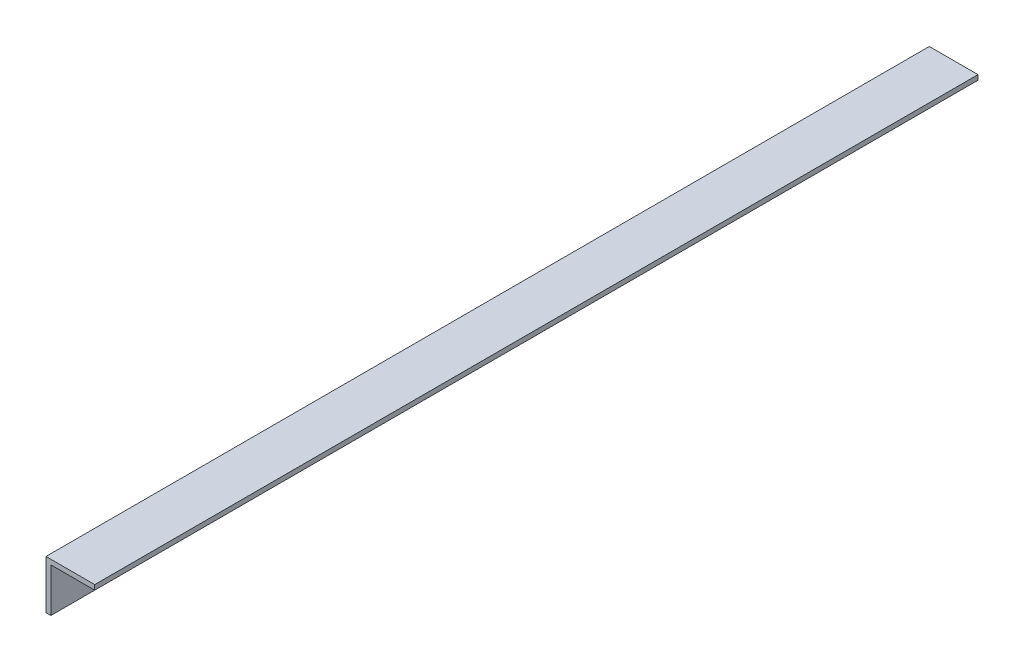
SolidWorks part; units mm, degrees
material "6061 Alloy"
ref_plane "Front Plane" through (0, 0, 0) normal (0, 0, 1) x (1, 0, 0)
ref_plane "Top Plane" through (0, 0, 0) normal (0, 1, 0) x (1, 0, 0)
ref_plane "Right Plane" through (0, 0, 0) normal (1, 0, 0) x (0, 0, -1)
sketch "Sketch1" plane through (0, 0, 0) normal (0, 0, 1) x (1, 0, 0)
  line L0 (-25.4, 0) -> (0, 0)
  line L2 (-25.4, -25.4) -> (-25.4, 0)
  dimension "D1" = 25.4
  dimension "D2" = 25.4
extrude "Extrude-Thin1" add sketch "Sketch1" along normal blind 460.375 thin contours L2 L0
